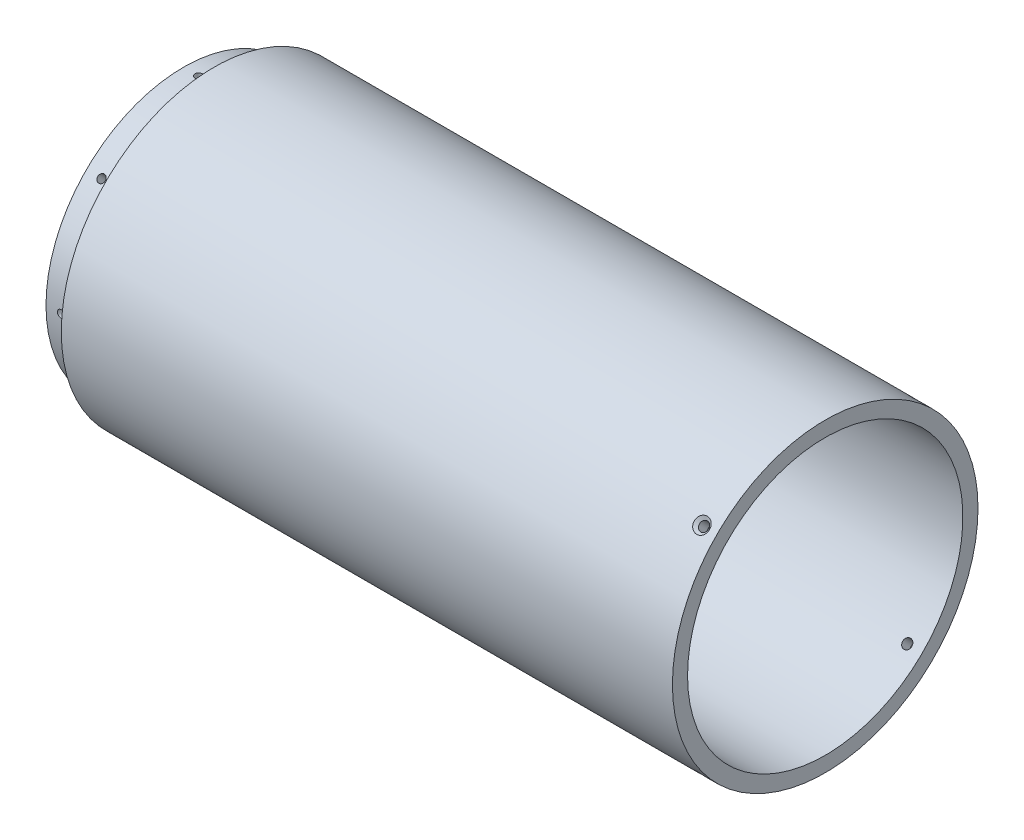
SolidWorks part; units mm, degrees
material "POM Acetal Copolymer"
ref_plane "Front Plane" through (0, 0, 0) normal (0, 0, 1) x (1, 0, 0)
ref_plane "Top Plane" through (0, 0, 0) normal (0, 1, 0) x (1, 0, 0)
ref_plane "Right Plane" through (0, 0, 0) normal (1, 0, 0) x (0, 0, -1)
sketch "Sketch1" plane through (0, 0, 0) normal (0, 0, 1) x (1, 0, 0)
  line L0 (0, 90.1) -> (-390, 90.1)
  line L1 (0, 100) -> (0, 90.1)
  line L2 (-171.7706, 0) -> (89.1379, 0) construction
  line L3 (-390, 90.1) -> (-390, 80)
  line L4 (-390, 80) -> (-420, 80)
  line L5 (-420, 80) -> (-420, 90)
  line L6 (-420, 90) -> (-400, 90)
  line L7 (-400, 90) -> (-400, 100)
  line L8 (-400, 100) -> (0, 100)
  dimension "D1" = 400
  dimension "D2" = 390
revolve "Revolve1" add sketch "Sketch1" angle 360 about L2
ref_plane "Plane1" through (0, 0, 100) normal (0, 0, 1) x (1, 0, 0)
ref_plane "Plane2" through (0, -100, 0) normal (0, 1, 0) x (-1, 0, 0)
ref_point "Point1"
ref_point "Point2"
ref_plane "Plane3" through (0, -70.7107, 70.7107) normal (0, -0.7071, 0.7071) x (1, 0, 0)
sketch "Sketch23" plane through (0, -70.7107, 70.7107) normal (0, -0.7071, 0.7071) x (1, 0, 0)
  line L0 (-171.7706, 0) -> (89.1379, 0) construction
  circle A0 centre (-10, 0) radius 3
extrude "Cut-Extrude23" cut sketch "Sketch23" against normal up to next
sketch "Sketch24" plane through (0, -70.7107, 70.7107) normal (0, -0.7071, 0.7071) x (1, 0, 0)
  circle A0 centre (-10, 0) radius 5
extrude "Cut-Extrude24" cut sketch "Sketch24" against normal up to next (190.1 mm away) draft 45
pattern_circular "CirPattern30" count 4 over 360 about axis through (-171.7706, 0, 0) along (1, 0, 0) of "Cut-Extrude24", "Cut-Extrude23"
sketch "Sketch25" plane through (0, -70.7107, 70.7107) normal (0, -0.7071, 0.7071) x (1, 0, 0)
  line L0 (-171.7706, 0) -> (89.1379, 0) construction
  line L1 (-420, 90) -> (-420, -90) construction
  circle A0 centre (-410, 0) radius 2.5
  dimension "D1" = 10
extrude "Cut-Extrude25" cut sketch "Sketch25" against normal up to next
pattern_circular "CirPattern31" count 8 over 360 about axis through (-171.7706, 0, 0) along (1, 0, 0) of "Cut-Extrude25"
